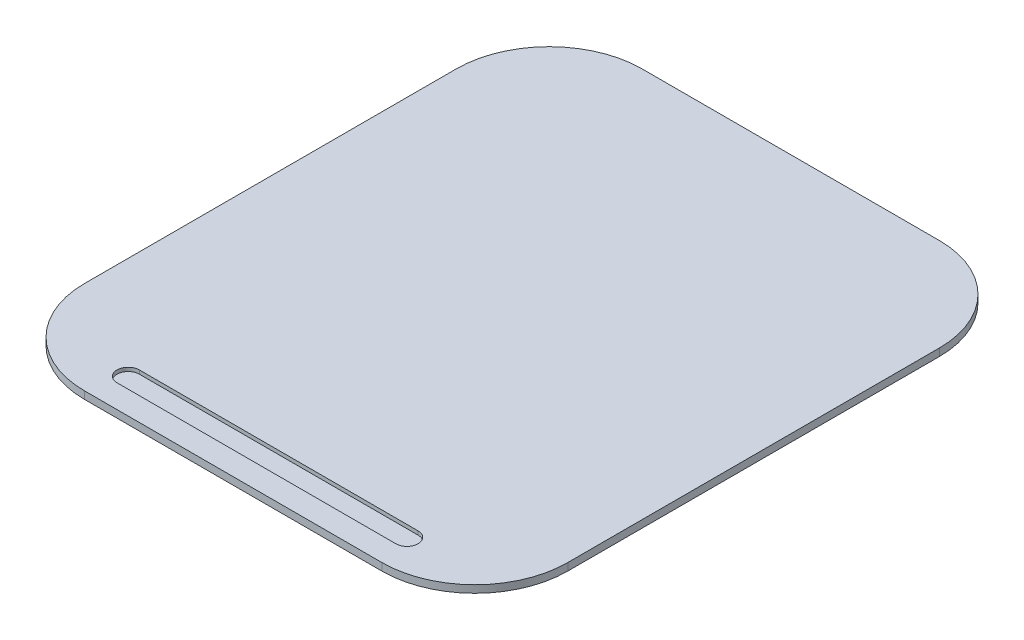
SolidWorks part; units mm, degrees
material "6063-O"
ref_plane "Plano frontal" through (0, 0, 0) normal (0, 0, 1) x (1, 0, 0)
ref_plane "Plano superior" through (0, 0, 0) normal (0, 1, 0) x (1, 0, 0)
ref_plane "Plano direito" through (0, 0, 0) normal (1, 0, 0) x (0, 0, -1)
sketch "Chapa inferior" plane through (0, 0, 0) normal (0, 1, 0) x (1, 0, 0)
  line L1 (-160, 300) -> (160, 300)
  line L2 (-260, 200) -> (-260, -200)
  line L3 (-160, -300) -> (160, -300)
  line L4 (260, 200) -> (260, -200)
  line L5 (-260, 300) -> (260, -300) construction
  line L6 (-260, -300) -> (260, 300) construction
  arc A0 (160, 300) -> (260, 200) centre (160, 200) cw
  arc A1 (160, -300) -> (260, -200) centre (160, -200) ccw
  arc A2 (-260, -200) -> (-160, -300) centre (-160, -200) ccw
  arc A3 (-160, 300) -> (-260, 200) centre (-160, 200) ccw
  point P0 (0, 0)
  dimension "D3" = 100
  dimension "D4" = 100
  dimension "D5" = 100
  dimension "D6" = 100
  dimension "D1" = 520
  dimension "D2" = 600
extrude "ChapaInferior" add sketch "Chapa inferior" along normal mid plane 8
sketch "Esboço2" plane through (0, 0, 0) normal (0, 1, 0) x (1, 0, 0)
  line L0 (-150, -263) -> (150, -263) construction
  line L1 (-150, -251) -> (150, -251)
  line L2 (-150, -275) -> (150, -275)
  line L4 (-160, -300) -> (160, -300) construction
  arc A0 (-150, -251) -> (-150, -275) centre (-150, -263) ccw
  arc A1 (150, -275) -> (150, -251) centre (150, -263) ccw
  point P2 (0, -263)
  point P9 (0, -300)
  dimension "D4" = 25
  dimension "D1" = 12
  dimension "D2" = 300
  dimension "D3" = 0
extrude "Corte-extrusão1" cut sketch "Esboço2" along normal through all
